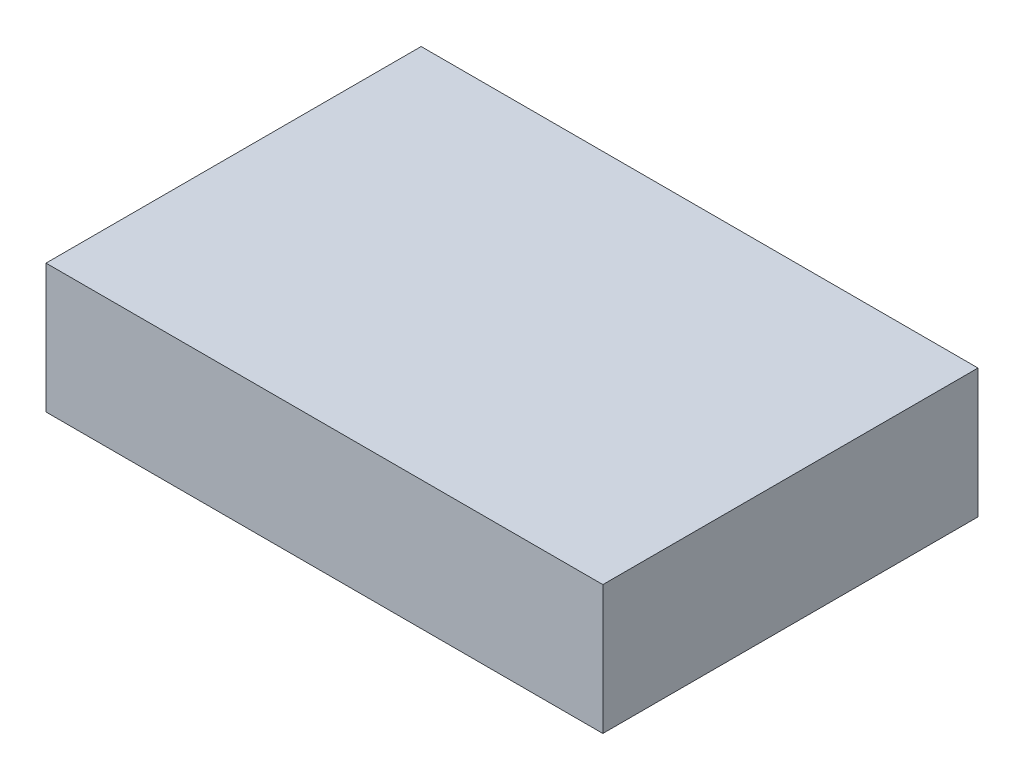
SolidWorks part; units mm, degrees
ref_plane "Front Plane" through (0, 0, 0) normal (0, 0, 1) x (1, 0, 0)
ref_plane "Top Plane" through (0, 0, 0) normal (0, 1, 0) x (1, 0, 0)
ref_plane "Right Plane" through (0, 0, 0) normal (1, 0, 0) x (0, 0, -1)
sketch "Sketch1" plane through (0, 0, 0) normal (0, 1, 0) x (1, 0, 0)
  line L0 (0, 0) -> (0, -32) construction
  line L1 (0, -32) -> (47.5, -32) construction
  line L3 (-47.5, 32) -> (47.5, 32)
  line L4 (-47.5, 32) -> (-47.5, -32)
  line L5 (-47.5, -32) -> (47.5, -32)
  line L6 (47.5, 32) -> (47.5, -32)
  line L7 (-47.5, 32) -> (47.5, -32) construction
  line L8 (-47.5, -32) -> (47.5, 32) construction
extrude "Boss-Extrude1" add sketch "Sketch1" along normal blind 22
